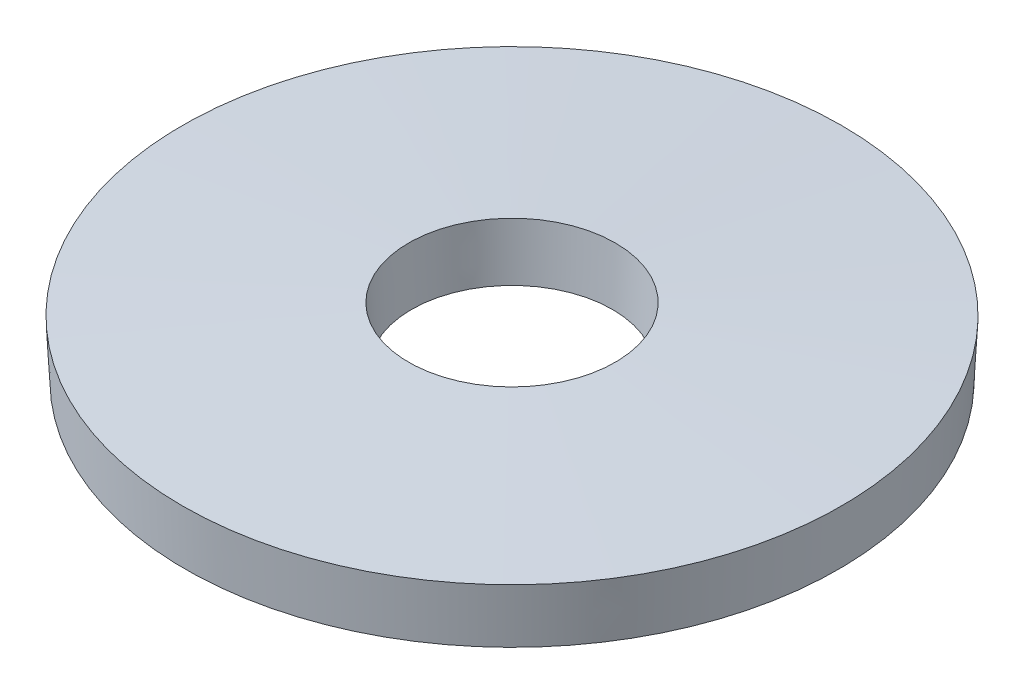
SolidWorks part; units mm, degrees
material "Plain Carbon Steel"
ref_plane "Front Plane" through (0, 0, 0) normal (0, 0, 1) x (1, 0, 0)
ref_plane "Top Plane" through (0, 0, 0) normal (0, 1, 0) x (1, 0, 0)
ref_plane "Right Plane" through (0, 0, 0) normal (1, 0, 0) x (0, 0, -1)
sketch "Sketch1" plane through (0, 0, 0) normal (1, 0, 0) x (0, 0, -1)
  line L0 (-20.6375, 0) -> (-6.35, 0.7157)
  line L1 (-6.35, 0.7157) -> (-6.5279, 4.2672)
  line L2 (-6.5279, 4.2672) -> (-20.8154, 3.5515)
  line L3 (-20.8154, 3.5515) -> (-20.6375, 0)
  line L4 (0, 0) -> (0, 8.9815) construction
  dimension "D1" = 3.556
  dimension "D2" = 41.275
  dimension "D3" = 4.2672
  dimension "D4" = 12.7
revolve "Revolve1" add sketch "Sketch1" angle 360 about L4
